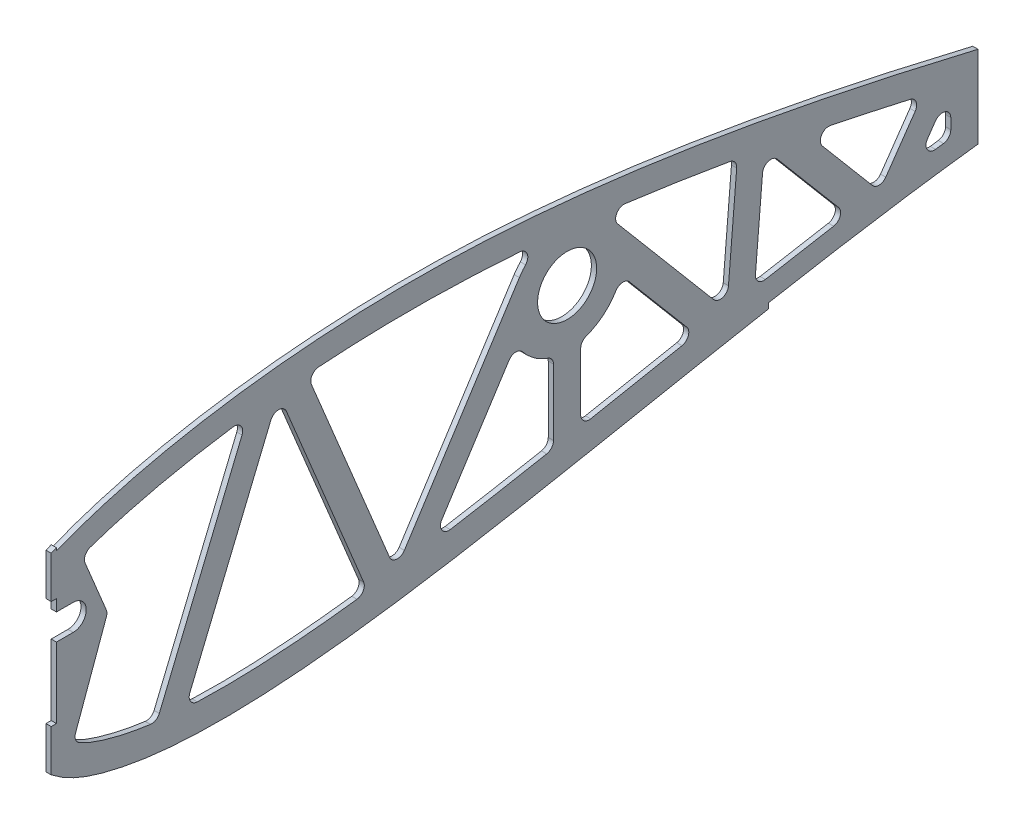
SolidWorks part; units mm, degrees
material "CARBON FIBERR"
ref_plane "Front Plane" through (0, 0, 0) normal (0, 0, 1) x (1, 0, 0)
ref_plane "Top Plane" through (0, 0, 0) normal (0, 1, 0) x (1, 0, 0)
ref_plane "Right Plane" through (0, 0, 0) normal (1, 0, 0) x (0, 0, -1)
sketch "Sketch1" plane through (0, 0, 0) normal (1, 0, 0) x (0, 0, -1)
  line L12 (616.0961, 24.8993) -> (616.0961, -28.6308)
  line L13 (612.9211, 25.6596) -> (612.9211, -29.0098)
  line L14 (50.8, 40.3347) -> (50.8, -76.0967)
  line L15 (50.8, 40.3347) -> (53.975, 40.3347)
  line L16 (53.975, 40.3347) -> (53.975, -76.0967)
  line L17 (53.975, -76.0967) -> (50.8, -76.0967)
  line L18 (95.6896, -76.9862) -> (53.975, 23.7218) construction
  line L19 (69.3029, 29.8597) -> (84.9398, -7.8913)
  line L20 (114.8686, -80.1456) -> (169.9226, 52.7666)
  line L21 (132.1089, -81.6665) -> (188.71, 54.9808)
  line L22 (188.71, 54.9808) -> (242.8499, -75.7243)
  line L23 (205.9214, 56.5717) -> (259.7538, -73.3914)
  line L24 (259.7538, -73.3914) -> (334.7518, 43.1671)
  line L25 (332.7321, 9.5164) -> (281.5278, -70.0631)
  line L26 (363.695, 24.544) -> (363.695, -55.3834)
  line L27 (355.44, -8.8683) -> (355.44, -56.9538)
  line L28 (371.95, -8.8683) -> (371.95, -53.8017)
  line L29 (389.9835, 46.7577) -> (460.5427, -36.7446)
  line L30 (460.5427, -36.7446) -> (466.9469, 39.4845)
  line L31 (396.343, 13.6517) -> (441.9147, -40.2795)
  line L32 (477.3741, -33.6114) -> (483.2683, 36.5484)
  line L33 (483.2683, 36.5484) -> (534.158, -23.6763)
  line L34 (596.4111, 12.6034) -> (596.4111, -14.4424)
  line L35 (509.0547, 31.6118) -> (553.2021, -20.6338)
  line L36 (553.2021, -20.6338) -> (579.0933, 16.6155)
  line L37 (575.6363, -17.2851) -> (596.4111, 12.6034)
  line L38 (114.8686, -80.1456) -> (114.8686, 43.0283) construction
  line L39 (53.975, 14.9347) -> (50.8, 14.9347)
  line L40 (53.975, -50.6967) -> (50.8, -50.6967)
  line L41 (53.975, 7.8913) -> (64.135, 7.8913)
  line L42 (64.135, -7.8913) -> (53.975, -7.8913)
  line L43 (0, 0) -> (64.135, 0) construction
  line L44 (64.1351, -65.3604) -> (84.9398, -7.8913)
  line L49 (53.975, 40.3347) -> (53.975, 41.651)
  line L50 (485.9211, -48.8296) -> (485.9211, -45.6021)
  circle A0 centre (363.695, 24.544) radius 34.417
  circle A2 centre (363.695, 24.544) radius 17.907 construction
  circle A3 centre (363.695, 24.544) radius 17.907
  arc A4 (64.135, 7.8913) -> (64.135, -7.8913) centre (64.135, 0) cw
  spline S0 degree 1 poles (674.1753, -6.5897) (16.921, -1.2798) knots 0 0 1 1 construction
  spline S1 degree 1 poles (16.921, -1.2798) (674.1753, -6.5897) knots 0 0 1 1 construction
  spline S2 degree 3 poles (7.7579, -2917.8825) (921.9308, -1.429) (846.8289, -45.9907) (789.3572, -23.4586) (777.0615, -18.6436) (760.5817, -13.0401) (739.9968, -7.1233) (715.5772, -0.3798) (687.647, 7.013) (656.6835, 14.9584) (623.1589, 23.2583) (587.5492, 31.6944) (550.3192, 40.0262) (511.9148, 48.0016) (472.7617, 55.3745) (433.2622, 61.9128) (393.7959, 67.4048) (354.7199, 71.6552) (316.357, 74.5357) (278.9313, 75.7536) (242.6994, 75.3938) (207.8706, 73.5467) (174.7468, 70.259) (143.6014, 65.7682) (114.7621, 60.1875) (88.5345, 53.6285) (65.199, 46.2382) (45.0006, 38.1339) (28.1586, 29.5092) (14.871, 20.5578) (6.1442, 12.3133) (1.9481, 6.1765) (0.6391, 3.0841) (0.217, 1.668) (-2.5675, -12.5382) (41.9664, -30.9514) (-2987.9583, 245.302) knots -0.191188 -0.191188 -0.191188 -0.191188 0.003802 0.014472 0.030564 0.051299 0.077028 0.107574 0.142399 0.180921 0.222525 0.266591 0.312515 0.35971 0.407632 0.455773 0.503669 0.550901 0.597096 0.641976 0.685512 0.727353 0.767354 0.805169 0.840471 0.872937 0.902335 0.928425 0.951113 0.970253 0.985871 0.993982 0.996753 0.997907 0.999293 1.048576 1.048576 1.048576 1.048576 only from (802.1511, -28.0117) to (0, 0) construction
  spline S3 degree 3 poles (802.1511, -28.0117) (801.1372, -27.7105) (797.2784, -26.5642) (789.3572, -23.4586) (777.0615, -18.6436) (760.5817, -13.0401) (739.9968, -7.1233) (715.5772, -0.3798) (687.647, 7.013) (656.6835, 14.9584) (623.1589, 23.2583) (587.5492, 31.6944) (550.3192, 40.0262) (511.9148, 48.0016) (472.7617, 55.3745) (433.2622, 61.9128) (393.7959, 67.4048) (354.7199, 71.6552) (316.357, 74.5357) (278.9313, 75.7536) (242.6994, 75.3938) (207.8706, 73.5467) (174.7468, 70.259) (143.6014, 65.7682) (114.7621, 60.1875) (88.5345, 53.6285) (65.199, 46.2382) (45.0006, 38.1339) (28.1586, 29.5092) (14.871, 20.5578) (6.1442, 12.3133) (1.9481, 6.1765) (0.6391, 3.0841) (0.217, 1.668) (0.0426, 0.7778) (0.0107, 0.1963) (0, 0) knots 0 0 0 0 0.003802 0.014472 0.030564 0.051299 0.077028 0.107574 0.142399 0.180921 0.222525 0.266591 0.312515 0.35971 0.407632 0.455773 0.503669 0.550901 0.597096 0.641976 0.685512 0.727353 0.767354 0.805169 0.840471 0.872937 0.902335 0.928425 0.951113 0.970253 0.985871 0.993982 0.996753 0.997907 0.999293 1 1 1 1
  spline S4 degree 3 poles (-2990.4271, -217.8416) (65.0803, 52.4472) (-4.4846, 21.0798) (0.5702, -4.3968) (2.5361, -10.6164) (7.9982, -20.5501) (16.1137, -34.185) (25.7513, -48.9002) (36.932, -62.9388) (49.3364, -75.9186) (65.2269, -85.625) (84.4528, -91.7174) (106.8521, -96.1515) (132.5109, -98.5722) (161.1944, -99.0924) (192.7613, -97.7042) (227.0382, -94.5118) (263.8348, -89.6638) (302.9215, -83.3884) (344.0178, -75.9778) (386.7768, -67.7807) (430.7746, -59.2023) (475.4963, -50.6638) (520.3353, -42.6036) (564.5889, -35.4228) (607.4709, -29.4733) (648.1275, -25.0145) (685.6676, -22.1862) (719.1968, -21.0048) (747.8303, -21.2786) (770.6884, -22.8547) (787.0914, -25.0735) (864.3121, -38.8992) (925.0612, -103.9188) (1620.626, 2853.5132) knots -0.081662 -0.081662 -0.081662 -0.081662 0.001821 0.004613 0.009135 0.024676 0.044153 0.064937 0.086321 0.107138 0.1276 0.150893 0.177565 0.207668 0.241222 0.278203 0.318526 0.362031 0.408465 0.457479 0.508614 0.561296 0.614835 0.668438 0.721214 0.772202 0.820393 0.864766 0.904324 0.938132 0.965242 0.98469 0.99621 1.240504 1.240504 1.240504 1.240504 only from (0, 0) to (802.1511, -28.0117) construction
  spline S5 degree 3 poles (0, 0) (0.0175, -0.519) (0.0617, -1.8338) (0.5702, -4.3968) (2.5361, -10.6164) (7.9982, -20.5501) (16.1137, -34.185) (25.7513, -48.9002) (36.932, -62.9388) (49.3364, -75.9186) (65.2269, -85.625) (84.4528, -91.7174) (106.8521, -96.1515) (132.5109, -98.5722) (161.1944, -99.0924) (192.7613, -97.7042) (227.0382, -94.5118) (263.8348, -89.6638) (302.9215, -83.3884) (344.0178, -75.9778) (386.7768, -67.7807) (430.7746, -59.2023) (475.4963, -50.6638) (520.3353, -42.6036) (564.5889, -35.4228) (607.4709, -29.4733) (648.1275, -25.0145) (685.6676, -22.1862) (719.1968, -21.0048) (747.8303, -21.2786) (770.6884, -22.8547) (787.0914, -25.0735) (796.8423, -26.8193) (801.0977, -27.7751) (802.1511, -28.0117) knots 0 0 0 0 0.001821 0.004613 0.009135 0.024676 0.044153 0.064937 0.086321 0.107138 0.1276 0.150893 0.177565 0.207668 0.241222 0.278203 0.318526 0.362031 0.408465 0.457479 0.508614 0.561296 0.614835 0.668438 0.721214 0.772202 0.820393 0.864766 0.904324 0.938132 0.965242 0.98469 0.99621 1 1 1 1
  spline S6 degree 3 poles (674.1753, -6.5897) (649.7599, -0.2901) (622.3859, 6.5069) (593.5263, 13.2816) (587.7544, 14.6234) (581.9811, 15.9566) (567.7907, 19.2002) (545.1621, 24.2098) (521.1016, 29.2278) (504.3659, 32.5445) (494.9815, 34.3547) (487.1741, 35.8291) (480.5497, 37.0516) (475.1099, 38.0366) (469.6687, 39.0093) (451.5132, 42.1901) (420.5122, 47.1551) (377.9644, 52.6996) (335.2278, 56.808) (292.5797, 59.0729) (250.8362, 59.182) (220.5316, 57.7505) (203.0493, 56.3451) (197.3102, 55.8319) (191.5746, 55.2845) (185.641, 54.6644) (179.5095, 53.9652) (173.1136, 53.1909) (166.7971, 52.3618) (156.6113, 50.9151) (143.2035, 48.7925) (129.7116, 46.2466) (118.2872, 43.8191) (110.8334, 42.1158) (98.3391, 39.0128) (86.4236, 35.6519) (76.1811, 32.289) (70.9132, 30.4496) (67.2755, 29.1263) (62.1129, 27.1518) (57.0278, 25.075) (50.8613, 22.3524) (45.5651, 19.8172) (40.4582, 17.1351) (36.2273, 14.7294) (32.1607, 12.2133) (28.3393, 9.6044) (25.351, 7.321) (23.1242, 5.4511) (21.5854, 4.0598) (20.1757, 2.6724) (19.114, 1.5212) (18.3353, 0.6057) (17.7805, -0.0853) (17.2981, -0.7285) (17.0486, -1.0874) (16.921, -1.2798) knots 0.155194 0.155194 0.155194 0.155194 0.246284 0.256996 0.262352 0.267708 0.278419 0.314992 0.351564 0.367429 0.376821 0.386213 0.396241 0.401255 0.406269 0.416298 0.468152 0.520311 0.572471 0.624631 0.67679 0.7254 0.735995 0.741293 0.74659 0.757185 0.763236 0.769287 0.780886 0.786685 0.807189 0.830945 0.837465 0.850505 0.859349 0.885429 0.896801 0.900061 0.906581 0.911509 0.921174 0.927694 0.937589 0.944109 0.950628 0.957148 0.963668 0.970188 0.973448 0.976708 0.979968 0.983228 0.984858 0.986488 0.988118 0.989748 0.989748 0.989748 0.989748
  spline S7 degree 3 poles (16.921, -1.2798) (17.0093, -1.5448) (17.19, -2.0553) (17.6331, -3.1942) (18.2894, -4.6876) (19.256, -6.6431) (20.3822, -8.7441) (21.6602, -11.0142) (23.4762, -14.1834) (25.7473, -18.0602) (28.5409, -22.6836) (31.3959, -27.2669) (34.2831, -31.7404) (38.1978, -37.5368) (42.2532, -43.049) (46.5634, -48.4005) (49.9429, -52.3614) (53.3245, -56.0977) (57.7199, -60.5154) (61.4721, -63.5972) (65.0957, -66.0024) (67.6528, -67.5536) (70.9645, -69.3063) (75.0579, -71.1004) (79.4782, -72.7137) (84.1618, -74.1578) (89.2106, -75.5071) (93.4904, -76.5179) (96.87, -77.2398) (101.8777, -78.2436) (106.9748, -79.0967) (113.0844, -79.9358) (116.6135, -80.3601) (122.3252, -80.9575) (128.0838, -81.4315) (135.1987, -81.8533) (146.3733, -82.3218) (163.0537, -82.4033) (184.9011, -81.5215) (206.8401, -79.8528) (224.7577, -77.9718) (238.1727, -76.3382) (245.6662, -75.3591) (251.3004, -74.5911) (256.9354, -73.8026) (263.3826, -72.8673) (270.2349, -71.8348) (277.8984, -70.6479) (293.3084, -68.1777) (319.0638, -63.75) (342.5798, -59.3904) (356.8161, -56.6932) (359.5679, -56.1702) (362.3194, -55.6462) (365.0706, -55.1208) (367.8221, -54.5939) (370.5739, -54.0663) (383.0029, -51.6775) (405.4402, -47.3212) (429.6385, -42.6276) (445.0925, -39.671) (451.4526, -38.4613) (457.5113, -37.3141) (463.3454, -36.2168) (468.9547, -35.1697) (474.5663, -34.1276) (482.87, -32.5987) (501.5888, -29.2055) (520.6985, -25.8846) (537.3278, -23.1542) (543.6739, -22.1329) (550.0238, -21.1252) (556.8678, -20.063) (564.2077, -18.9537) (571.8234, -17.8283) (579.0931, -16.7877) (586.0154, -15.829) (592.9429, -14.8917) (607.1307, -13.0418) (627.1639, -10.6793) (651.3483, -8.2941) (666.5667, -7.0983) (674.1753, -6.5897) knots 0.007773 0.007773 0.007773 0.007773 0.00942 0.011067 0.014361 0.017654 0.020948 0.024242 0.027536 0.034123 0.04071 0.047298 0.053885 0.060473 0.073648 0.080235 0.086822 0.09341 0.099997 0.112858 0.116152 0.11976 0.126347 0.132934 0.139522 0.146109 0.152697 0.159621 0.162915 0.165872 0.179046 0.182475 0.189062 0.192356 0.203889 0.210476 0.218571 0.244921 0.27127 0.29762 0.32397 0.335715 0.345835 0.350895 0.355955 0.366075 0.374045 0.38056 0.39359 0.429369 0.472996 0.477927 0.480393 0.482858 0.487787 0.490251 0.492715 0.497644 0.534768 0.573013 0.584076 0.589878 0.59568 0.60566 0.61065 0.61564 0.625619 0.640166 0.68211 0.693308 0.698908 0.704507 0.715705 0.723025 0.730345 0.742492 0.748565 0.754638 0.766785 0.798265 0.824614 0.850964 0.850964 0.850964 0.850964
  spline S8 degree 1 poles (801.699, -29.5335) (1.5851, -0.0867) knots 0 0 1 1 construction
  spline S9 degree 3 poles (801.699, -29.5335) (800.6457, -29.2206) (798.5465, -28.5967) (794.3504, -27.1347) (789.2863, -25.1309) (783.2243, -22.7666) (775.1315, -19.7048) (764.9074, -16.174) (752.4918, -12.3573) (739.9685, -8.7957) (723.2358, -4.1293) (702.274, 1.5242) (677.057, 8.1057) (651.8012, 14.5306) (626.5025, 20.7838) (592.7127, 28.8755) (550.3576, 38.4751) (499.3109, 48.9424) (448.0173, 58.0896) (396.4682, 65.6088) (353.3039, 70.2129) (318.6809, 72.6741) (284.0077, 74.1322) (249.2913, 74.0496) (214.6347, 72.3269) (188.707, 70.136) (162.8708, 67.0342) (137.1737, 62.978) (111.6807, 57.8325) (90.6898, 52.4748) (74.137, 47.3991) (61.8822, 43.1309) (49.8415, 38.326) (38.0873, 32.8846) (28.6521, 27.6886) (21.4387, 23.0269) (16.2659, 19.2238) (11.3773, 15.0719) (7.7131, 11.2622) (5.1065, 7.951) (3.4213, 5.3575) (2.3138, 3.0747) (1.7977, 1.4601) (1.6474, 0.6881) (1.6067, 0.3026) (1.5919, 0.037) (1.5851, -0.0867) knots 0 0 0 0 0.003906 0.007812 0.015625 0.023438 0.03125 0.046875 0.0625 0.078125 0.09375 0.125 0.15625 0.1875 0.21875 0.25 0.3125 0.375 0.4375 0.5 0.5625 0.59375 0.625 0.6875 0.71875 0.75 0.78125 0.8125 0.84375 0.875 0.890625 0.90625 0.921875 0.9375 0.953125 0.960938 0.96875 0.976562 0.984375 0.988281 0.992188 0.996094 0.998047 0.999023 0.999512 1 1 1 1
  spline S10 degree 1 poles (3.1732, 0.1067) (802.8469, -24.9139) knots 0 0 1 1 construction
  spline S11 degree 3 poles (3.1732, 0.1067) (3.1819, -0.1521) (3.2011, -0.7036) (3.2467, -1.3257) (3.3354, -1.9569) (3.5122, -2.8621) (3.8204, -4.0789) (4.4162, -6.0041) (5.3425, -8.4272) (7.094, -12.2508) (9.7119, -17.0201) (13.0504, -22.7925) (16.4406, -28.4677) (21.0946, -35.9752) (27.1466, -45.1637) (33.7501, -53.8739) (39.4068, -60.5874) (43.8008, -65.4663) (48.3936, -70.0244) (54.8973, -75.4881) (64.0361, -81.1237) (76.0251, -85.8337) (88.754, -89.2337) (101.6501, -91.8371) (114.7087, -93.6633) (127.8778, -94.8443) (145.5183, -95.7216) (167.6295, -95.7019) (194.1715, -94.3241) (220.6668, -91.9192) (247.1006, -88.7182) (282.2622, -83.6318) (326.0721, -76.1243) (378.5138, -66.1663) (427.3837, -56.6179) (467.5708, -48.9466) (502.6305, -42.5412) (541.3347, -35.8673) (588.9974, -28.593) (642.1598, -22.2258) (686.701, -18.8601) (722.4487, -17.8536) (749.311, -18.1454) (771.7414, -19.7555) (787.3336, -21.9396) (795.0967, -23.2791) (799.5629, -24.1765) (801.7493, -24.6674) (802.8469, -24.9139) knots 0 0 0 0 0.000977 0.001953 0.00293 0.003906 0.005859 0.007812 0.011719 0.015625 0.023437 0.03125 0.039062 0.046875 0.0625 0.078125 0.085937 0.09375 0.101562 0.109375 0.125 0.140625 0.15625 0.171875 0.1875 0.203125 0.21875 0.25 0.28125 0.3125 0.34375 0.375 0.4375 0.5 0.5625 0.612294 0.643544 0.6875 0.75 0.8125 0.875 0.90625 0.9375 0.96875 0.984375 0.992187 0.996094 1 1 1 1
  dimension "D2" = 3.175
  dimension "D3" = 50.8
  dimension "D4" = 3.175
  dimension "D5" = 16.51
  dimension "D1" = 186.055
  dimension "D7" = 16.51
  dimension "D8" = 16.51
  dimension "D9" = 16.51
  dimension "D10" = 16.51
  dimension "D11" = 16.51
  dimension "D12" = 16.51
  dimension "D13" = 16.51
  dimension "D14" = 16.51
  dimension "D15" = 16.51
  dimension "D16" = 16.51
  dimension "D17" = 45
  dimension "D18" = 45
  dimension "D19" = 45
  dimension "D20" = 45
  dimension "D21" = 75
  dimension "D22" = 8.255
  dimension "D23" = 22.5
  dimension "D24" = 25.4
  dimension "D25" = 25.4
  dimension "D27" = 127
  dimension "D29" = 10.16
  dimension "D6" = 16.51
  dimension "D26" = 1.5875
  dimension "D28" = 3.175
extrude "Boss-Extrude1" add sketch "Sketch1" along normal mid plane 3.175
fillet "Fillet1" radius 5.08 31 edges at (0, -17.2851, -575.6363) (0, -14.4424, -596.4111) (0, 12.6034, -596.4111) (0, 16.6155, -579.0933) (0, 31.6118, -509.0547) (0, -20.6338, -553.2021) (0, -36.7446, -460.5427) (0, -33.6114, -477.3741) (0, -23.6763, -534.158) (0, 36.5484, -483.2683) (0, 39.4845, -466.9469) (0, 55.4246, -348.4991) (0, 51.652, -384.9009) (0, 13.6517, -396.343) (0, -8.8683, -371.95) (0, -8.8683, -355.44) (0, 9.5164, -332.7321) (0, -40.2795, -441.9147) (0, -53.8017, -371.95) (0, -56.9538, -355.44) (0, -70.0631, -281.5278) (0, -73.3914, -259.7538) (0, -75.7243, -242.8499) (0, 56.5717, -205.9214) (0, 54.9808, -188.71) (0, 52.7666, -169.9226) (0, -81.6665, -132.1089) (0, 29.8597, -69.3029) (0, -80.1456, -114.8686) (0, -65.3604, -64.1351) (0, -7.8913, -84.9398)
